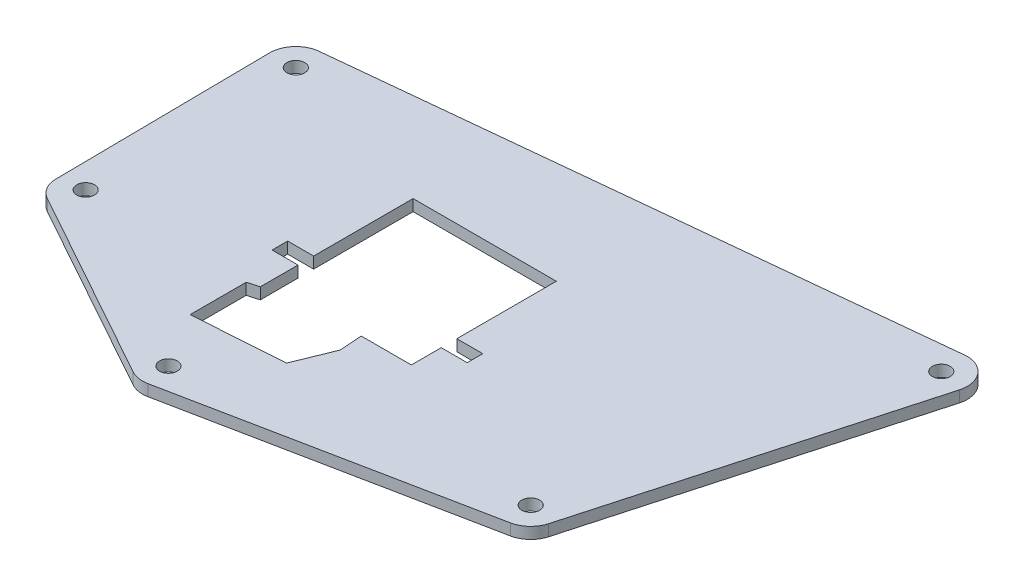
SolidWorks part; units mm, degrees
ref_plane "Front Plane" through (0, 0, 0) normal (0, 0, 1) x (1, 0, 0)
ref_plane "Top Plane" through (0, 0, 0) normal (0, 1, 0) x (1, 0, 0)
ref_plane "Right Plane" through (0, 0, 0) normal (1, 0, 0) x (0, 0, -1)
sketch "Sketch2" plane through (0, 0, 0) normal (0, 1, 0) x (1, 0, 0)
  line L0 (602.2882, -78.7714) -> (811.0416, 604.0302) construction
sketch "Sketch1" plane through (0, 0, 0) normal (0, 1, 0) x (1, 0, 0)
  line L0 (-6.823, -7.4882) -> (47.147, -37.4723)
  line L1 (0.8879, 1.746) -> (0.8879, 1.9982) construction
  line L2 (52.0977, -38.2428) -> (136.3593, -21.3082)
  line L3 (141.9163, -16.1444) -> (166.9034, 73.5687)
  line L4 (-4.3661, 66.0537) -> (159.1821, 82.7288)
  line L5 (-10.9695, 58.6673) -> (-10.2889, -1.673)
  line L6 (0.8879, 57.4592) -> (0.8879, 57.626) construction
  arc A1 (-1.7855, 60.3977) -> (-2.8, 56.5177) centre (0.8879, 57.626) ccw construction
  circle A3 centre (159.9176, 75.5145) radius 2.4892
  circle A4 centre (134.9305, -14.1987) radius 2.4892
  circle A5 centre (50.6688, -31.1332) radius 2.4892
  arc A7 (-10.2889, -1.673) -> (-6.823, -7.4882) centre (-3.55, -1.597) ccw
  arc A8 (47.147, -37.4723) -> (52.0977, -38.2428) centre (50.6688, -31.1332) ccw
  arc A9 (136.3593, -21.3082) -> (141.9163, -16.1444) centre (134.9305, -14.1987) ccw
  arc A10 (166.9034, 73.5687) -> (159.1821, 82.7288) centre (159.9176, 75.5145) ccw
  arc A11 (-4.3661, 66.0537) -> (-10.9695, 58.6673) centre (-3.7196, 58.8308) ccw
  circle A12 centre (-3.7196, 58.8308) radius 2.4892
  circle A13 centre (50.6688, -31.1332) radius 7.2517 construction
  circle A14 centre (134.9305, -14.1987) radius 7.2517 construction
  circle A15 centre (159.9176, 75.5145) radius 7.2517 construction
  circle A16 centre (-3.5081, -0.086) radius 2.4892
  circle A17 centre (-3.7196, 58.8308) radius 7.2517 construction
  point P2 (-6.8392, -6.0494)
  point P32 (-10.9621, 58.8657)
  point P36 (0, 0)
  point P37 (-3.7104, 66.1174)
  point P38 (-3.7104, 66.1174)
  point P39 (-4.3661, 66.0537)
  dimension "D2" = 160.0326
  dimension "D3" = 4.7625
  dimension "D7" = 4.7625
  dimension "D6" = 4.9784
  dimension "D1" = 4.7625
  dimension "D4" = 152.073
  dimension "D5" = 101.7661
  dimension "D9" = 4.7625
extrude "Boss-Extrude1" add sketch "Sketch1" along normal blind 3.175
sketch "Sketch3" plane through (0, 3.175, 0) normal (0, 1, 0) x (1, 0, 0)
  line L0 (41.2559, -15.6784) -> (66.4681, -13.884)
  line L1 (66.4681, -13.884) -> (70.7748, -3.2967)
  line L2 (70.7748, -3.2967) -> (70.0328, 7.1286)
  line L3 (70.0328, 7.1286) -> (58.5655, 6.3125)
  line L4 (58.5655, 6.3125) -> (53.862, 3.5831)
  line L5 (53.862, 3.5831) -> (41.2559, 0)
  line L6 (41.2559, 0) -> (41.2559, -15.6784)
extrude "trigger cutout" cut sketch "Sketch3" against normal blind 3.175
sketch "Sketch4" plane through (0, 3.175, 0) normal (0, 1, 0) x (1, 0, 0)
  line L0 (64.3283, 3.0581) -> (64.3283, 43.5581) construction
  line L1 (44.3283, 43.5581) -> (84.3283, 43.5581)
  line L2 (44.3283, 43.5581) -> (44.3283, 15.7581)
  line L3 (64.3283, 3.0581) -> (84.3283, 3.0581)
  line L4 (84.3283, 43.5581) -> (84.3283, 15.7581)
  line L5 (37.0783, 15.7581) -> (44.3283, 15.7581)
  line L6 (37.0783, 15.7581) -> (37.0783, 11.4098)
  line L7 (37.0783, 11.4098) -> (44.3283, 11.4098)
  line L8 (91.5783, 15.7581) -> (91.5783, 11.4098)
  line L9 (44.3283, 3.0581) -> (44.3283, -2.1684)
  line L10 (44.3283, -2.1684) -> (64.3283, -2.1684)
  line L11 (64.3283, -2.1684) -> (64.3283, 3.0581)
  line L12 (84.3283, 11.4098) -> (91.5783, 11.4098)
  line L13 (84.3283, 15.7581) -> (91.5783, 15.7581)
  line L14 (44.3283, 11.4098) -> (44.3283, 3.0581)
  line L15 (84.3283, 11.4098) -> (84.3283, 3.0581)
  dimension "D1" = 40.5
  dimension "D2" = 40
  dimension "D3" = 54.5
  dimension "D4" = 27.8
extrude "servo cutout" cut sketch "Sketch4" against normal blind 3.175
